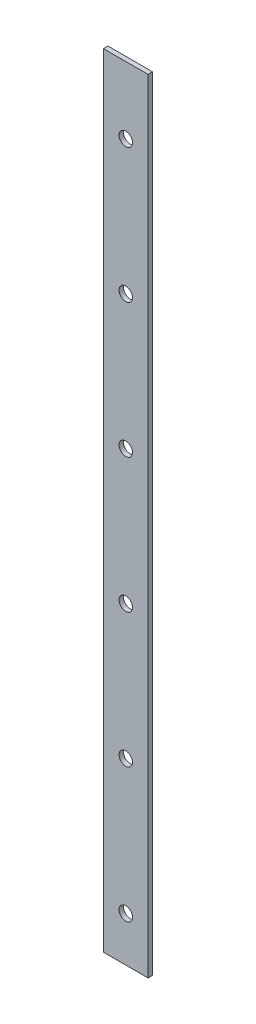
SolidWorks part; units mm, degrees
material "6061 Legierung"
ref_plane "Ebene vorne" through (0, 0, 0) normal (0, 0, 1) x (1, 0, 0)
ref_plane "Ebene oben" through (0, 0, 0) normal (0, 1, 0) x (1, 0, 0)
ref_plane "Ebene rechts" through (0, 0, 0) normal (1, 0, 0) x (0, 0, -1)
sketch "Skizze1" plane through (0, 0, 0) normal (0, 0, 1) x (1, 0, 0)
  line L0 (0, 0) -> (0, 434.3011) construction
  line L2 (-10, 0) -> (10, 0)
  line L3 (-10, 0) -> (-10, 350)
  line L4 (-10, 350) -> (10, 350)
  line L5 (10, 0) -> (10, 350)
  dimension "D1" = 350
  dimension "D2" = 20
extrude "Aufsatz-Linear austragen1" add sketch "Skizze1" along normal blind 2
sketch "Skizze2" plane through (0, 0, 2) normal (0, 0, 1) x (1, 0, 0)
  line L0 (0, 0) -> (0, 64.8533) construction
  line L1 (-10, 0) -> (10, 0) construction
  circle A0 centre (0, 20) radius 3
  dimension "D2" = 6
  dimension "D1" = 20
extrude "Schnitt-Linear austragen1" cut sketch "Skizze2" against normal blind 10
pattern_linear "Lineares Muster1" count 6 spacing 60 along (0, 1, 0) of "Schnitt-Linear austragen1"
